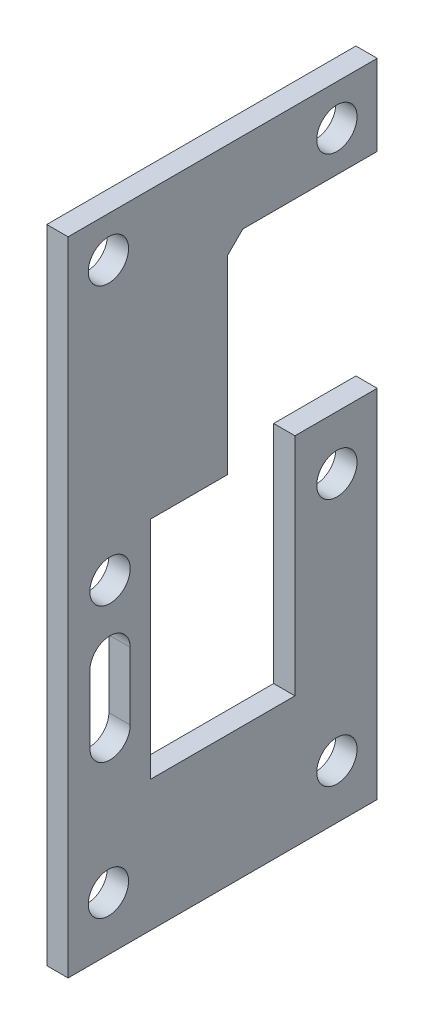
SolidWorks part; units mm, degrees
material "6063-O"
ref_plane "Front" through (0, 0, 0) normal (0, 0, 1) x (1, 0, 0)
ref_plane "Top" through (0, 0, 0) normal (0, 1, 0) x (1, 0, 0)
ref_plane "Right" through (0, 0, 0) normal (1, 0, 0) x (0, 0, -1)
sketch "Sketch1" plane through (0, 0, 0) normal (1, 0, 0) x (0, 0, -1)
  line L1 (23, 47.76) -> (-23, 47.76)
  line L2 (23, 47.76) -> (23, -47.76)
  line L3 (23, -47.76) -> (-23, -47.76)
  line L4 (-23, 47.76) -> (-23, -47.76)
  line L5 (23, 47.76) -> (-23, -47.76) construction
  line L6 (23, -47.76) -> (-23, 47.76) construction
  point P0 (0, 0)
  dimension "D1" = 95.52
  dimension "D2" = 46
extrude "Boss-Extrude1" add sketch "Sketch1" along normal blind 3.175
sketch "Sketch2" plane through (3.175, 0, 0) normal (1, 0, 0) x (0, 0, -1)
  line L1 (23, 35.76) -> (3, 35.76)
  line L2 (23, 35.76) -> (23, 5.24)
  line L3 (23, 5.24) -> (3, 5.24)
  line L4 (3, 35.76) -> (3, 5.24)
  line L5 (23, 35.76) -> (3, 5.24) construction
  line L6 (23, 5.24) -> (3, 35.76) construction
  line L7 (23, -47.76) -> (23, 47.76) construction
  line L8 (23, 47.76) -> (-23, 47.76) construction
  point P0 (13, 20.5)
  dimension "D1" = 12
  dimension "D2" = 30.52
  dimension "D3" = 20
  dimension "D4" = 0
extrude "Cut-Extrude1" cut sketch "Sketch2" against normal through all
hole_wizard "Ø6.0mm Clearance Dowel Hole1" positions "Sketch5" profile "Sketch4" hole size "Ø6.0" standard "ANSI Metric" end condition through all
sketch "Sketch5" plane through (3.175, 0, 0) normal (1, 0, 0) x (0, 0, -1)
  line L0 (3, 5.24) -> (23, 5.24) construction
  line L1 (23, -47.76) -> (23, 5.24) construction
  line L2 (-23, -47.76) -> (23, -47.76) construction
  point P0 (17, -2.76)
  point P2 (17, -39.76)
  dimension "D1" = 8
  dimension "D2" = 6
  dimension "D3" = 6
  dimension "D4" = 8
sketch "Sketch4" plane through (3.175, -2.76, -17) normal (0, 1, 0) x (0, 0, -1)
  line L0 (0, 0) -> (0, 3.175)
  line L1 (0, 3.175) -> (3, 3.175)
  line L2 (3, 3.175) -> (3, 0)
  line L5 (3, 0) -> (0, 0)
  line L11 (0, -6.35) -> (0, 107.95) construction
  dimension "Thru Hole Dia." = 6
  dimension "Thru Hole Depth" = 3.175
hole_wizard "Ø6.0mm Dowel Hole1" positions "Sketch7" profile "Sketch8" hole size "Ø6.0" standard "ANSI Metric" end condition through all
sketch "Sketch7" plane through (3.175, 0, 0) normal (1, 0, 0) x (0, 0, -1)
  line L0 (23, 35.76) -> (23, 47.76) construction
  line L1 (23, 47.76) -> (-23, 47.76) construction
  line L2 (-23, 47.76) -> (-23, -47.76) construction
  line L3 (-23, -47.76) -> (23, -47.76) construction
  point P0 (17, 41.76)
  point P2 (-17, 41.76)
  point P11 (-17, -39.76)
  dimension "D1" = 6
  dimension "D2" = 6
  dimension "D3" = 6
  dimension "D4" = 6
  dimension "D5" = 8
  dimension "D6" = 6
sketch "Sketch8" plane through (3.175, 41.76, -17) normal (0, 1, 0) x (0, 0, -1)
  line L0 (0, 0) -> (0, 3.175)
  line L1 (0, 3.175) -> (3, 3.175)
  line L2 (3, 3.175) -> (3, 0)
  line L5 (3, 0) -> (0, 0)
  line L11 (0, -6.35) -> (0, 107.95) construction
  dimension "Thru Hole Dia." = 6
  dimension "Thru Hole Depth" = 3.175
sketch "Sketch9" plane through (3.175, 0, 0) normal (1, 0, 0) x (0, 0, -1)
  line L0 (3, 35.76) -> (0.7019, 33.4619)
  line L1 (0.7019, 33.4619) -> (0.7019, 5.24)
  line L2 (0.7019, 5.24) -> (3, 5.24)
  line L3 (3, 5.24) -> (3, 35.76)
  line L4 (23, 35.76) -> (3, 35.76) construction
  dimension "D1" = 45
  dimension "D2" = 90
  dimension "D3" = 3.25
  dimension "D4" = 0
extrude "Cut-Extrude2" cut sketch "Sketch9" against normal through all
sketch "Sketch10" plane through (3.175, 0, 0) normal (1, 0, 0) x (0, 0, -1)
  line L0 (23, 47.76) -> (-23, 47.76) construction
  line L1 (10.76, 5.24) -> (-10.76, 5.24)
  line L2 (10.76, 5.24) -> (10.76, -3.28)
  line L3 (10.76, -3.28) -> (-10.76, -3.28)
  line L4 (-10.76, 5.24) -> (-10.76, -3.28)
  line L5 (10.76, 5.24) -> (-10.76, -3.28) construction
  line L6 (10.76, -3.28) -> (-10.76, 5.24) construction
  line L8 (23, -47.76) -> (23, 5.24) construction
  point P0 (0, 0.98)
  dimension "D1" = 42.52
  dimension "D2" = 8.52
  dimension "D3" = 23
  dimension "D4" = 21.52
extrude "Cut-Extrude3" cut sketch "Sketch10" against normal through all
sketch "Sketch11" plane through (3.175, 0, 0) normal (1, 0, 0) x (0, 0, -1)
  line L0 (-10.76, -3.28) -> (10.76, -3.28) construction
  line L1 (-10.76, -3.28) -> (10.76, -3.28)
  line L2 (-10.76, -3.28) -> (-10.76, -28.28)
  line L3 (-10.76, -28.28) -> (10.76, -28.28)
  line L4 (10.76, -3.28) -> (10.76, -28.28)
  dimension "D1" = 25
  dimension "D2" = 21.52
  dimension "D3" = 0
  dimension "D4" = 10.76
extrude "Cut-Extrude4" cut sketch "Sketch11" against normal through all
sketch "Sketch14" plane through (3.175, 0, 0) normal (1, 0, 0) x (0, 0, -1)
  line L0 (-16.76, -9.77) -> (-16.76, -19.77) construction
  line L1 (-13.76, -9.77) -> (-13.76, -19.77)
  line L2 (-19.76, -9.77) -> (-19.76, -19.77)
  line L3 (-23, -47.76) -> (23, -47.76) construction
  line L4 (-10.76, 5.24) -> (-10.76, -28.28) construction
  circle A0 centre (-16.76, 0.39) radius 3
  arc A1 (-13.76, -9.77) -> (-19.76, -9.77) centre (-16.76, -9.77) ccw
  arc A2 (-19.76, -19.77) -> (-13.76, -19.77) centre (-16.76, -19.77) ccw
  point P4 (-16.76, -14.77)
  point P13 (-16.76, -6.77)
  dimension "D1" = 6
  dimension "D2" = 10.16
  dimension "D3" = 48.15
  dimension "D4" = 6
  dimension "D5" = 3
  dimension "D6" = 10
  dimension "D7" = 6
extrude "Cut-Extrude5" cut sketch "Sketch14" against normal through all
